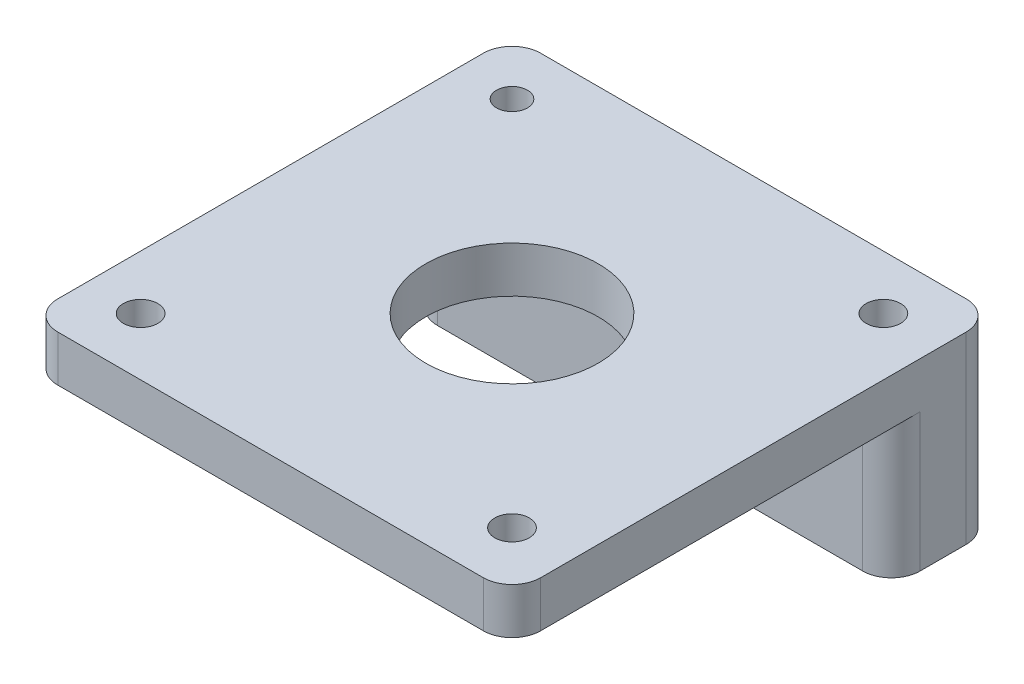
SolidWorks part; units mm, degrees
ref_plane "Front Plane" through (0, 0, 0) normal (0, 0, 1) x (1, 0, 0)
ref_plane "Top Plane" through (0, 0, 0) normal (0, 1, 0) x (1, 0, 0)
ref_plane "Right Plane" through (0, 0, 0) normal (1, 0, 0) x (0, 0, -1)
sketch "Sketch1" plane through (0, 0, 0) normal (0, 1, 0) x (1, 0, 0)
  line L1 (0, 0) -> (42, 0)
  line L2 (0, 0) -> (0, 9)
  line L3 (0, 9) -> (42, 9)
  line L4 (42, 0) -> (42, 9)
  dimension "D1" = 9
  dimension "D2" = 42
extrude "Boss-Extrude1" add sketch "Sketch1" along normal blind 12
sketch "Sketch2" plane through (0, 12, 0) normal (0, 1, 0) x (1, 0, 0)
  line L1 (0, 9) -> (42, 9)
  line L2 (0, 9) -> (0, -33)
  line L3 (0, -33) -> (42, -33)
  line L4 (42, 9) -> (42, -33)
  dimension "D1" = 42
extrude "Boss-Extrude2" add sketch "Sketch2" along normal blind 4
fillet "Fillet1" radius 2.5 1 edges at (0, 14, 33)
fillet "Fillet2" radius 2.5 1 edges at (0, 8, -9)
fillet "Fillet3" radius 2.5 1 edges at (0, 6, 0)
fillet "Fillet4" radius 2.5 1 edges at (42, 14, 33)
fillet "Fillet5" radius 2.5 1 edges at (42, 6, 0)
fillet "Fillet6" radius 2.5 1 edges at (42, 8, -9)
sketch "Sketch3" plane through (0, 16, 0) normal (0, 1, 0) x (1, 0, 0)
  circle A0 centre (20.85, -11.85) radius 7.5
  circle A1 centre (4.7, -28) radius 1.5
  circle A2 centre (37, -28) radius 1.5
  circle A3 centre (37, 4.3) radius 1.5
  circle A4 centre (4.7, 4.3) radius 1.3423
  dimension "D1" = 15
extrude "Cut-Extrude1" cut sketch "Sketch3" against normal blind 20
sketch "Sketch4" plane through (0, 0, 0) normal (0, -1, 0) x (1, 0, 0)
  circle A0 centre (4.7, -4.3) radius 3
  circle A1 centre (37, -4.3) radius 3
  dimension "D1" = 6
  dimension "D2" = 6
extrude "Cut-Extrude2" cut sketch "Sketch4" against normal blind 5
sketch "Sketch5" plane through (0, 0, -9) normal (0, 0, -1) x (-1, 0, 0)
  line L0 (-42, 0) -> (-42, 16) construction
  circle A0 centre (-27, 8) radius 4
  point P4 (-42, 8)
  dimension "D1" = 8
  dimension "D2" = 15
extrude "Cut-Extrude3" cut sketch "Sketch5" against normal blind 9
